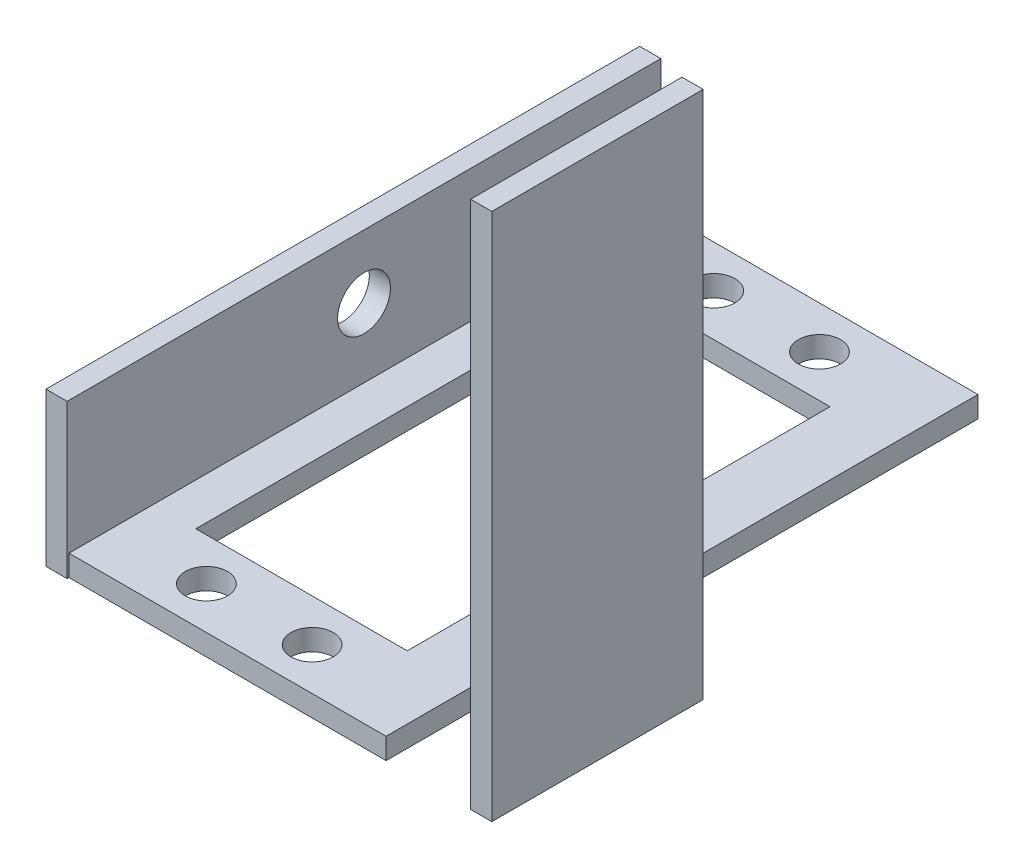
SolidWorks part; units mm, degrees
ref_plane "Front Plane" through (0, 0, 0) normal (0, 0, 1) x (1, 0, 0)
ref_plane "Top Plane" through (0, 0, 0) normal (0, 1, 0) x (1, 0, 0)
ref_plane "Right Plane" through (0, 0, 0) normal (1, 0, 0) x (0, 0, -1)
sketch "Sketch1" plane through (0, 0, 0) normal (0, 1, 0) x (1, 0, 0)
  line L1 (-10.3859, -11.5013) -> (9.6141, -11.5013)
  line L2 (-10.3859, -11.5013) -> (-10.3859, -19.5013)
  line L3 (-10.3859, -19.5013) -> (9.6141, -19.5013)
  line L4 (9.6141, -11.5013) -> (9.6141, -19.5013)
  line L5 (-10.3859, 36.4987) -> (9.6141, 36.4987)
  line L6 (-10.3859, 36.4987) -> (-10.3859, 28.4987)
  line L7 (-10.3859, 28.4987) -> (9.6141, 28.4987)
  line L8 (9.6141, 36.4987) -> (9.6141, 28.4987)
  circle A0 centre (4.6141, -15.5013) radius 2
  circle A1 centre (-5.3859, -15.5013) radius 2
  circle A2 centre (4.6141, 32.4987) radius 2
  circle A3 centre (-5.3859, 32.4987) radius 2
  dimension "D5" = 5
  dimension "D9" = 40
  dimension "D1" = 20
  dimension "D2" = 20
  dimension "D3" = 8
  dimension "D4" = 8
  dimension "D6" = 5
  dimension "D7" = 5
  dimension "D8" = 5
  dimension "D10" = 48
extrude "Boss-Extrude1" add sketch "Sketch1" along normal blind 2
sketch "Sketch6" plane through (9.6141, 0, 0) normal (1, 0, 0) x (0, 0, -1)
  line L1 (-19.5013, 2) -> (36.4987, 2)
  line L2 (-19.5013, 2) -> (-19.5013, 0)
  line L3 (-19.5013, 0) -> (36.4987, 0)
  line L4 (36.4987, 2) -> (36.4987, 0)
extrude "Boss-Extrude5" add sketch "Sketch6" along normal blind 6
sketch "Sketch10" plane through (-10.3859, 0, 0) normal (-1, 0, 0) x (0, 0, 1)
  line L1 (-36.4987, 2) -> (19.5013, 2)
  line L2 (-36.4987, 2) -> (-36.4987, 0)
  line L3 (-36.4987, 0) -> (19.5013, 0)
  line L4 (19.5013, 2) -> (19.5013, 0)
extrude "Boss-Extrude7" add sketch "Sketch10" along normal blind 4
sketch "Sketch11" plane through (-14.3859, 0, 0) normal (-1, 0, 0) x (0, 0, 1)
  line L1 (-36.4987, 0) -> (19.6765, 0)
  line L2 (-36.4987, 0) -> (-36.4987, 14.5283)
  line L3 (-36.4987, 14.5283) -> (19.6765, 14.5283)
  line L4 (19.6765, 0) -> (19.6765, 14.5283)
extrude "Boss-Extrude8" add sketch "Sketch11" along normal blind 2
sketch "Sketch12" plane through (-16.3859, 0, 0) normal (-1, 0, 0) x (0, 0, 1)
  line L0 (19.6765, 14.5283) -> (-36.4987, 14.5283) construction
  circle A0 centre (-8.4111, 8.5283) radius 2.5
  dimension "D1" = 6
extrude "Cut-Extrude3" cut sketch "Sketch12" against normal blind 2
sketch "Sketch13" plane through (15.6141, 0, 0) normal (1, 0, 0) x (0, 0, -1)
  line L0 (-19.5013, 2) -> (-19.5013, 0) construction
  line L1 (-11.5013, 42) -> (8.4987, 42)
  line L2 (-11.5013, 42) -> (-11.5013, -8)
  line L3 (-11.5013, -8) -> (8.4987, -8)
  line L4 (8.4987, 42) -> (8.4987, -8)
  line L5 (36.4987, 2) -> (-19.5013, 2) construction
  dimension "D1" = 50
  dimension "D2" = 20
  dimension "D3" = 8
  dimension "D4" = 40
extrude "Boss-Extrude9" add sketch "Sketch13" along normal blind 2
